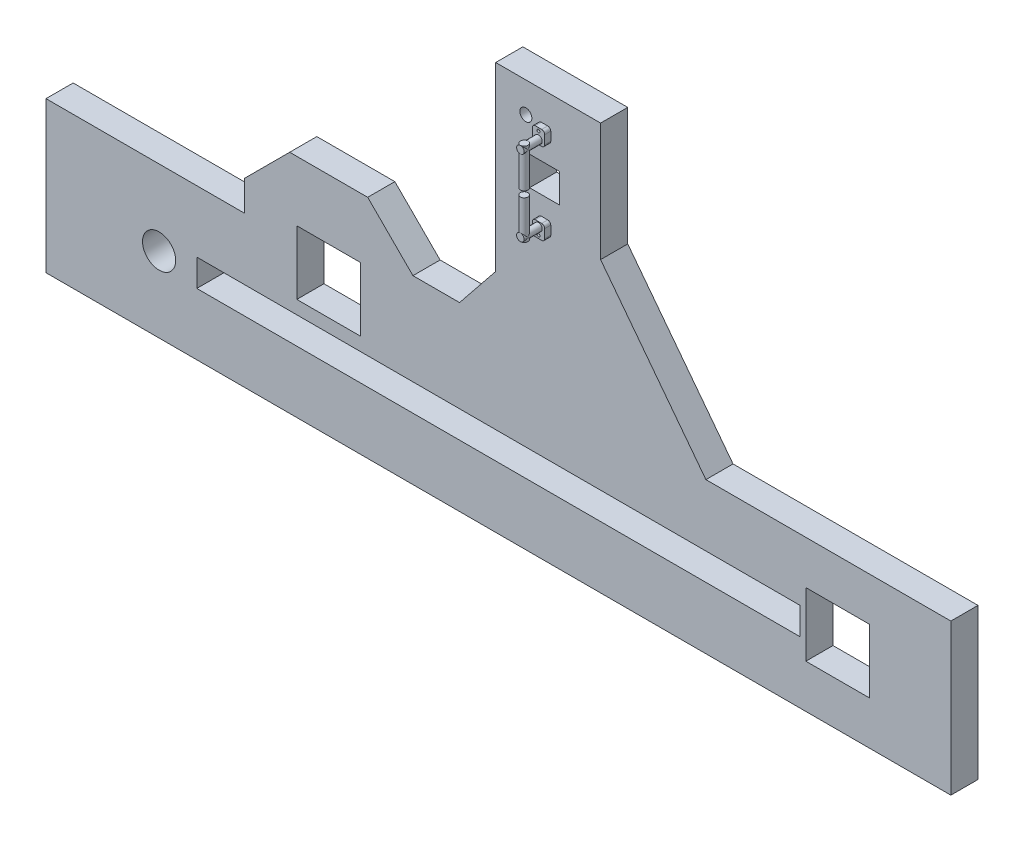
SolidWorks part; units mm, degrees
ref_plane "Piano frontale" through (0, 0, 0) normal (0, 0, 1) x (1, 0, 0)
ref_plane "Piano superiore" through (0, 0, 0) normal (0, 1, 0) x (1, 0, 0)
ref_plane "Piano destro" through (0, 0, 0) normal (1, 0, 0) x (0, 0, -1)
sketch "Schizzo1" plane through (0, 0, 0) normal (0, 0, 1) x (1, 0, 0)
  line L1 (-300, -50) -> (300, -50)
  line L2 (-300, -50) -> (-300, 50)
  line L3 (-300, 50) -> (300, 50)
  line L4 (300, -50) -> (300, 50)
  line L5 (-300, -50) -> (300, 50) construction
  line L6 (-300, 50) -> (300, -50) construction
  point P0 (0, 0)
  dimension "D1" = 600
  dimension "D2" = 100
extrude "Estrusione-Estrusione1" add sketch "Schizzo1" along normal blind 18
sketch "Schizzo2" plane through (0, 0, 18) normal (0, 0, 1) x (1, 0, 0)
  line L0 (-300, 0) -> (300, 0) construction
  line L1 (-300, 50) -> (-300, -50) construction
  line L2 (300, -50) -> (300, 50) construction
  line L4 (-200, -9) -> (200, -9)
  line L5 (-200, -9) -> (-200, 9)
  line L6 (-200, 9) -> (200, 9)
  line L7 (200, -9) -> (200, 9)
  line L8 (-200, -9) -> (200, 9) construction
  line L9 (-200, 9) -> (200, -9) construction
  point P6 (0, 0)
  dimension "D1" = 400
  dimension "D2" = 18
extrude "Taglio-Estrusione1" cut sketch "Schizzo2" against normal blind 18
sketch "Schizzo3" plane through (0, 0, 18) normal (0, 0, 1) x (1, 0, 0)
  line L0 (-200, 0) -> (-300, 0) construction
  line L1 (-200, 9) -> (-200, -9) construction
  line L2 (-300, 50) -> (-300, -50) construction
  line L3 (200, 0) -> (300, 0) construction
  line L4 (200, -9) -> (200, 9) construction
  line L5 (300, -50) -> (300, 50) construction
  circle A0 centre (-225, 0) radius 11
  dimension "D1" = 25
  dimension "D2" = 22
extrude "Taglio-Estrusione2" cut sketch "Schizzo3" against normal blind 18
mirror "Specchia1" about plane through (0, 0, 0) normal (1, 0, 0) of "Taglio-Estrusione2"
sketch "Schizzo4" plane through (0, 0, 18) normal (0, 0, 1) x (1, 0, 0)
  line L0 (0, 50) -> (0, -50) construction
  line L1 (300, 50) -> (-300, 50) construction
  line L2 (-300, -50) -> (300, -50) construction
  line L3 (-135, 50) -> (-135, -50) construction
  line L5 (200, 9) -> (-200, 9) construction
  line L7 (-133.7001, 17.85) -> (-91.4001, 17.85)
  line L8 (-133.7001, 17.85) -> (-133.7001, 60.15)
  line L9 (-133.7001, 60.15) -> (-91.4001, 60.15)
  line L10 (-91.4001, 17.85) -> (-91.4001, 60.15)
  line L11 (-133.7001, 17.85) -> (-91.4001, 60.15) construction
  line L12 (-133.7001, 60.15) -> (-91.4001, 17.85) construction
  circle A0 centre (-225, 0) radius 11 construction
  circle A1 centre (-112.5501, 39) radius 25 construction
  point P10 (-135, 0)
  dimension "D1" = 90
  dimension "D2" = 50
  dimension "D3" = 30
  dimension "D4" = 42.3
  dimension "D5" = 42.3
sketch "Schizzo7" plane through (0, 0, 18) normal (0, 0, 1) x (1, 0, 0)
  line L0 (-112.5501, 39) -> (-112.5501, 159.7672) construction
  line L1 (300, 50) -> (-300, 50) construction
  line L2 (-168.423, 100) -> (-56.6771, 100)
  line L3 (-168.423, 100) -> (-168.423, 50)
  line L4 (-168.423, 50) -> (-56.6771, 50)
  line L5 (-56.6771, 100) -> (-56.6771, 50)
  line L6 (-168.423, 100) -> (-56.6771, 50) construction
  line L7 (-168.423, 50) -> (-56.6771, 100) construction
  point P3 (-112.5501, 75)
  dimension "D1" = 50
extrude "Estrusione-Estrusione2" add sketch "Schizzo7" against normal up to surface (18 mm away) up to face at (214, 0, 0)
extrude "Taglio-Estrusione4" cut sketch "Schizzo4" against normal blind 18
chamfer "Smusso1" distance 30 angle 45 2 edges at (-56.6771, 100, 9) (-168.423, 100, 9)
ref_plane "Piano1" through (-56.6771, 50, 18) normal (-1, 0, 0) x (0, 0, 1)
sketch "Schizzo9" plane through (0, 0, 18) normal (0, 0, 1) x (1, 0, 0)
  line L0 (-1.8169, 99.8404) -> (-1.8169, 219.8404)
  line L1 (300, 50) -> (-56.6771, 50) construction
  line L2 (-1.8169, 219.8404) -> (38.1831, 219.8404)
  line L3 (38.1831, 219.8404) -> (38.1831, 99.8404)
  line L4 (-1.8169, 99.8404) -> (-41.8169, 50)
  line L5 (18.1831, 219.8404) -> (18.1831, 50) construction
  line L6 (38.1831, 99.8404) -> (78.1831, 50)
  circle A0 centre (18.1831, 199.8404) radius 4
  circle A1 centre (18.1831, 134.7504) radius 4
  dimension "D1" = 65.09
  dimension "D3" = 40
  dimension "D4" = 120
  dimension "D6" = 84.7504
extrude "Estrusione-Estrusione3" add sketch "Schizzo9" against normal blind 18
sketch "Schizzo10" plane through (0, 0, 18) normal (0, 0, 1) x (1, 0, 0)
  line L0 (-56.6771, 70) -> (-25.7656, 70)
  line L1 (-1.8169, 99.8404) -> (-41.8169, 50) construction
  line L2 (-56.6771, 70) -> (-56.6771, 50)
  line L3 (-56.6771, 50) -> (-41.8169, 50)
  line L4 (-41.8169, 50) -> (-25.7656, 70)
extrude "Estrusione-Estrusione4" add sketch "Schizzo10" against normal blind 18 contours L0 L4 L3 L2
sketch "Schizzo11" plane through (0, 0, 18) normal (0, 0, 1) x (1, 0, 0)
  line L1 (203.85, 21.15) -> (246.15, 21.15)
  line L2 (203.85, 21.15) -> (203.85, -21.15)
  line L3 (203.85, -21.15) -> (246.15, -21.15)
  line L4 (246.15, 21.15) -> (246.15, -21.15)
  line L5 (203.85, 21.15) -> (246.15, -21.15) construction
  line L6 (203.85, -21.15) -> (246.15, 21.15) construction
  point P0 (225, 0)
  dimension "D1" = 42.3
  dimension "D2" = 42.3
extrude "Taglio-Estrusione5" cut sketch "Schizzo11" against normal blind 28
sketch "Schizzo12" plane through (0, 0, 18) normal (0, 0, 1) x (1, 0, 0)
  line L0 (38.1831, 219.8404) -> (67.7431, 219.8404)
  line L1 (67.7431, 219.8404) -> (67.7431, 141.4244)
  line L2 (38.1831, 99.8404) -> (78.1831, 50) construction
  line L3 (67.7431, 63.0084) -> (38.1831, 99.8404)
  line L4 (38.1831, 99.8404) -> (38.1831, 219.8404)
  line L5 (67.7431, 141.4244) -> (137.5716, 50)
  line L6 (300, 50) -> (78.1831, 50) construction
  line L7 (137.5716, 50) -> (78.1831, 50)
  line L8 (78.1831, 50) -> (67.7431, 63.0084)
  dimension "D1" = 29.56
extrude "Estrusione-Estrusione5" add sketch "Schizzo12" against normal blind 18
sketch "Schizzo13" plane through (0, 0, 0) normal (0, 0, -1) x (-1, 0, 0)
  line L0 (-18.1831, 199.8404) -> (-18.1831, 134.7504) construction
  line L1 (1.8169, 219.8404) -> (-67.7431, 219.8404) construction
  line L2 (-87.8307, 167.2954) -> (34.3683, 167.2954) construction
  line L3 (-40.5031, 178.4204) -> (-20.6231, 178.4204)
  line L4 (-40.5031, 178.4204) -> (-40.5031, 159.1404)
  line L5 (-40.5031, 159.1404) -> (-20.6231, 159.1404)
  line L6 (-20.6231, 178.4204) -> (-20.6231, 159.1404)
  dimension "D1" = 19.28
  dimension "D2" = 41.42
  dimension "D3" = 19.88
  dimension "D4" = 2.44
extrude "Taglio-Estrusione6" cut sketch "Schizzo13" against normal blind 41
sketch "Schizzo14" plane through (0, 0, 18) normal (0, 0, 1) x (1, 0, 0)
  line L1 (26.4285, 200.6621) -> (34.6978, 200.6621)
  line L2 (26.4285, 200.6621) -> (26.4285, 190.8996)
  line L3 (26.4285, 190.8996) -> (34.6978, 190.8996)
  line L4 (34.6978, 200.6621) -> (34.6978, 190.8996)
  line L5 (26.4285, 200.6621) -> (34.6978, 190.8996) construction
  line L6 (26.4285, 190.8996) -> (34.6978, 200.6621) construction
  point P0 (30.5631, 195.7809)
extrude "Estrusione-Estrusione6" add sketch "Schizzo14" along normal blind 4 contours L1 L4 L3 L2
sketch "Schizzo15" plane through (0, 0, 22) normal (0, 0, 1) x (1, 0, 0)
fillet "Raccordo1" radius 2 4 edges at (34.6978, 190.8996, 20) (26.4285, 190.8996, 20) (34.6978, 200.6621, 20) (26.4285, 200.6621, 20)
sketch "Schizzo16" plane through (0, 0, 22) normal (0, 0, 1) x (1, 0, 0)
  line L0 (27.0143, 200.0763) -> (34.112, 191.4854) construction
  line L2 (34.112, 200.0763) -> (27.0143, 191.4854) construction
  arc A0 (28.4285, 200.6621) -> (26.4285, 198.6621) centre (28.4285, 198.6621) ccw construction
  arc A1 (32.6978, 190.8996) -> (34.6978, 192.8996) centre (32.6978, 192.8996) ccw construction
  arc A2 (34.6978, 198.6621) -> (32.6978, 200.6621) centre (32.6978, 198.6621) ccw construction
  arc A3 (26.4285, 192.8996) -> (28.4285, 190.8996) centre (28.4285, 192.8996) ccw construction
  circle A4 centre (30.5631, 198.684) radius 1
extrude "Taglio-Estrusione7" cut sketch "Schizzo16" against normal blind 4 contours A4
sketch "Schizzo17" plane through (0, 0, 18) normal (0, 0, 1) x (1, 0, 0)
  line L0 (20.6231, 178.4204) -> (40.5031, 159.1404) construction
  line L1 (40.5031, 178.4204) -> (20.6231, 159.1404) construction
  line L3 (16.3083, 168.7804) -> (45.3156, 168.7804) construction
ref_plane "Piano2" through (0, 168.8, 0) normal (0, 1, 0) x (1, 0, 0)
mirror "Specchia5" about plane through (0, 168.8, 0) normal (0, 1, 0) of "Estrusione-Estrusione6", "Taglio-Estrusione7", "Raccordo1"
sketch "Schizzo18" plane through (0, 0, 22) normal (0, 0, 1) x (1, 0, 0)
  line L0 (30.5631, 198.684) -> (30.5631, 191.6835) construction
  circle A0 centre (30.5631, 193.9531) radius 2.5
  dimension "D1" = 5
extrude "Estrusione-Estrusione7" add sketch "Schizzo18" along normal blind 12 contours A0
mirror "Specchia6" about plane through (0, 168.8, 0) normal (0, 1, 0) of "Estrusione-Estrusione7"
ref_plane "Piano3" through (0, 196.4531, 0) normal (0, 1, 0) x (1, 0, 0)
sketch "Schizzo19" plane through (0, 196.4531, 0) normal (0, 1, 0) x (1, 0, 0)
  line L0 (30.5631, -34) -> (30.5631, -25.1302) construction
  line L1 (28.0631, -34) -> (33.0631, -34) construction
  circle A0 centre (30.5631, -31.5) radius 2.5
  dimension "D1" = 5
extrude "Estrusione-Estrusione8" add sketch "Schizzo19" against normal blind 55.3
ref_plane "Piano4" through (0, 0, 34) normal (0, 0, 1) x (1, 0, 0)
sketch "Schizzo20" plane through (0, 0, 34) normal (0, 0, 1) x (1, 0, 0)
  line L0 (28.0631, 170.8) -> (33.0631, 170.8)
  line L1 (28.0631, 193.9531) -> (28.0631, 143.6469) construction
  line L2 (33.0631, 143.6469) -> (33.0631, 193.9531) construction
  line L3 (33.0631, 170.8) -> (33.0631, 166.8)
  line L4 (28.0631, 170.8) -> (28.0631, 166.8)
  line L7 (28.0631, 166.8) -> (33.0631, 166.8)
extrude "Taglio-Estrusione9" cut sketch "Schizzo20" against normal blind 55.3 contours L0 L3 L7 L4
